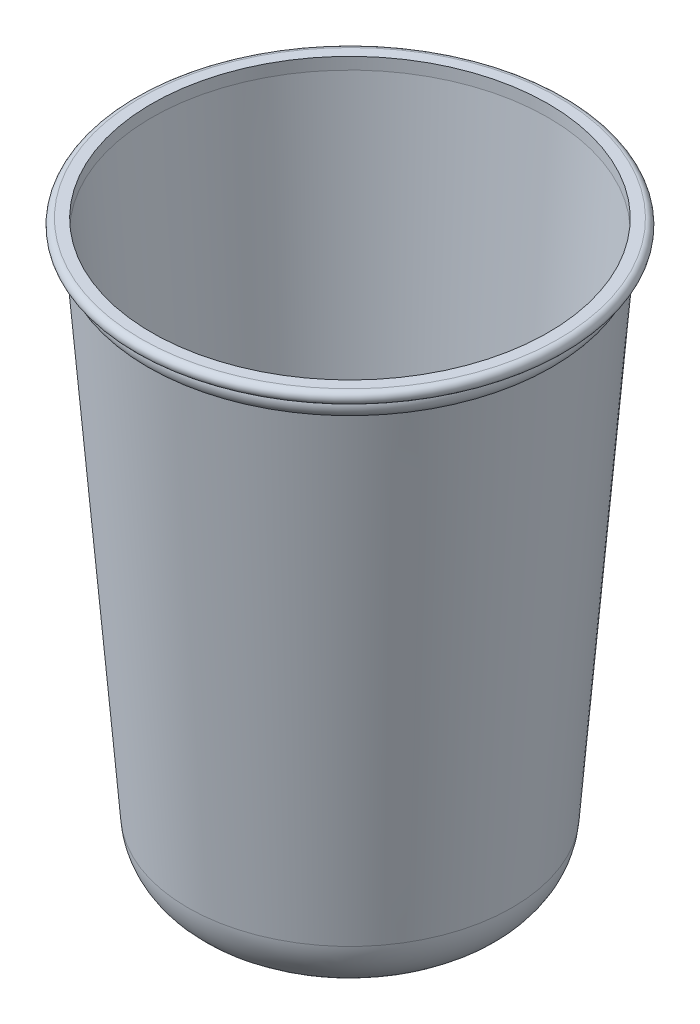
SolidWorks part; units mm, degrees
material "Ceramic Porcelain"
ref_plane "Front Plane" through (0, 0, 0) normal (0, 0, 1) x (1, 0, 0)
ref_plane "Top Plane" through (0, 0, 0) normal (0, 1, 0) x (1, 0, 0)
ref_plane "Right Plane" through (0, 0, 0) normal (1, 0, 0) x (0, 0, -1)
sketch "Sketch1" plane through (0, 0, 0) normal (0, 0, 1) x (1, 0, 0)
  line L0 (0, 0) -> (0, 120) construction
  line L1 (0, 120) -> (43.75, 120)
  line L2 (0, 0) -> (20.9981, 0)
  line L4 (0, 120) -> (0, 0)
  line L5 (33.9567, 11.9637) -> (42.113, 113.9606)
  line L7 (43.75, 118.75) -> (45, 118.75) construction
  line L8 (43.75, 117.5) -> (42.297, 117.5) construction
  line L9 (42.3961, 117.5) -> (43.75, 117.5)
  arc A0 (43.75, 117.5) -> (43.75, 120) centre (43.75, 118.75) ccw
  arc A1 (20.9981, 0) -> (33.9567, 11.9637) centre (20.9981, 13) ccw
  arc A2 (42.113, 113.9606) -> (42.3961, 117.5) centre (40.5, 115.8706) ccw
  point P4 (21, 0)
  point P6 (0, 120)
  point P12 (33, 0)
  dimension "D4" = 2.5
  dimension "D6" = 13
  dimension "D7" = 5
  dimension "D1" = 120
  dimension "D2" = 45
  dimension "D3" = 33
  dimension "D5" = 21
  dimension "D9" = 40.5
revolve "Revolve1" add sketch "Sketch1" angle 360 about L4
sketch "Sketch2" plane through (0, 0, 0) normal (0, -1, 0) x (1, 0, 0)
  circle A0 centre (0, 0) radius 16.5
  dimension "D1" = 33
extrude "Cut-Extrude1" cut sketch "Sketch2" against normal blind 5
fillet "Fillet1" radius 2 1 edges at (0, 0, -16.5)
fillet "Fillet2" radius 1 1 edges at (0, 5, -16.5)
sketch "Sketch4" plane through (0, 0, 0) normal (1, 0, 0) x (0, 0, -1)
  line L0 (0, 6.1731) -> (0, 120)
  line L1 (43.75, 120) -> (-43.75, 120) construction
  line L2 (0, 120) -> (41.5, 120)
  line L3 (41.5, 120) -> (41.5, 117.5)
  line L4 (-43.75, 117.5) -> (43.75, 117.5) construction
  line L5 (41.5, 117.5) -> (33.0606, 11.9637)
  line L6 (33.9567, 11.9637) -> (42.113, 113.9606) construction
  line L7 (0, 6.1731) -> (15.5, 6.1731)
  line L8 (17.6731, 4) -> (17.6731, 2)
  line L9 (16.5, 4) -> (-16.5, 4) construction
  line L10 (-33.9567, 11.9637) -> (33.9567, 11.9637) construction
  arc A0 (43.75, 117.5) -> (43.75, 120) centre (43.75, 118.75) ccw construction
  arc A1 (15.5, 6.1731) -> (17.6731, 4) centre (15.5, 4) cw
  arc A2 (17.6731, 2) -> (18.3169, 1.1936) centre (18.5, 2) ccw
  arc A3 (18.3169, 1.1936) -> (33.0606, 11.9637) centre (20.9981, 13) ccw
  arc A4 (20.9981, 0) -> (33.9567, 11.9637) centre (20.9981, 13) ccw construction
  arc A5 (16.5, 2) -> (18.5, 0) centre (18.5, 2) ccw construction
  arc A6 (16.5, 4) -> (15.5, 5) centre (15.5, 4) ccw construction
  point P21 (18.5, 2)
  point P22 (15.5, 4)
  dimension "D1" = 3.5
revolve "Cut-Revolve1" cut sketch "Sketch4" angle 360 about L0
